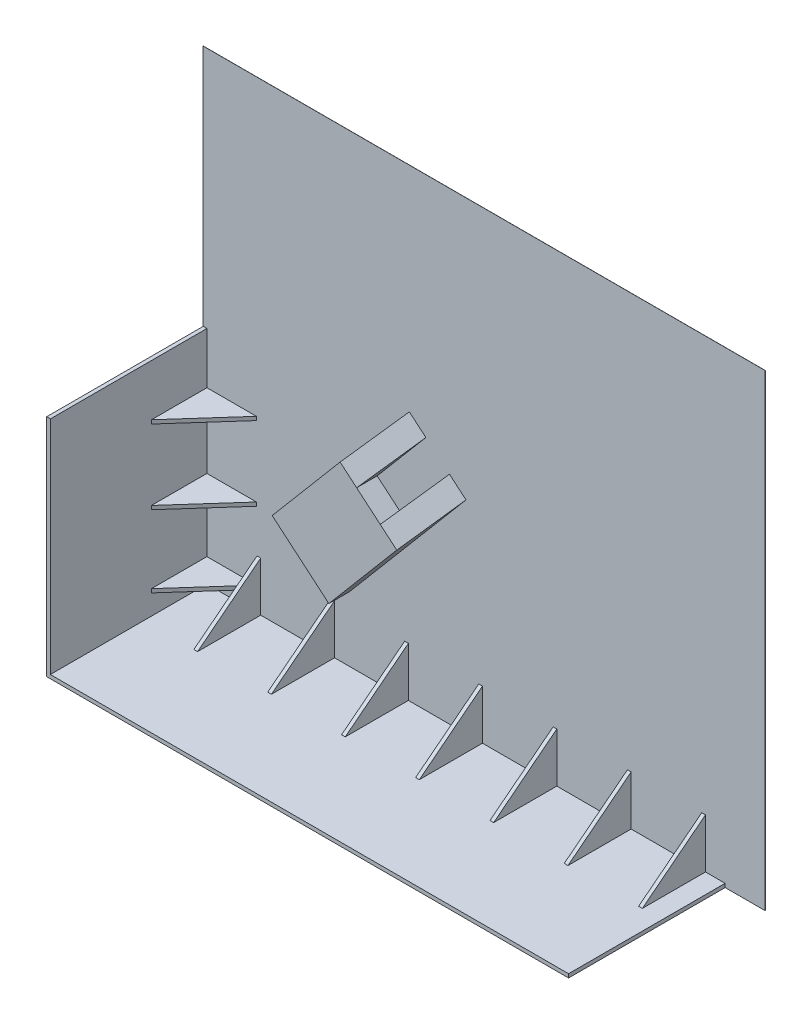
SolidWorks part; units mm, degrees
ref_plane "Front Plane" through (0, 0, 0) normal (0, 0, 1) x (1, 0, 0)
ref_plane "Top Plane" through (0, 0, 0) normal (0, 1, 0) x (1, 0, 0)
ref_plane "Right Plane" through (0, 0, 0) normal (1, 0, 0) x (0, 0, -1)
sketch "walls" plane through (0, 0, 0) normal (0, 0, 1) x (1, 0, 0)
  line L1 (0, 0) -> (4220, 0)
  line L2 (0, 0) -> (0, 30)
  line L3 (30, 30) -> (435, 30)
  line L4 (4220, 0) -> (4220, 30)
  line L5 (30, 1405) -> (30, 1820)
  line L6 (0, 30) -> (0, 1820)
  line L7 (0, 1820) -> (30, 1820)
  line L8 (30, 30) -> (30, 192.5)
  line L9 (30, 1405) -> (430, 1405)
  line L10 (30, 222.5) -> (30, 775)
  line L11 (30, 1375) -> (430, 1375)
  line L12 (430, 1405) -> (430, 1375)
  line L13 (30, 805) -> (430, 805)
  line L14 (30, 805) -> (30, 1375)
  line L15 (30, 775) -> (430, 775)
  line L16 (430, 805) -> (430, 775)
  line L17 (30, 222.5) -> (430, 222.5)
  line L18 (465, 30) -> (1032, 30)
  line L19 (30, 192.5) -> (430, 192.5)
  line L20 (430, 222.5) -> (430, 192.5)
  line L21 (1062, 30) -> (1629, 30)
  line L22 (435, 30) -> (435, 430)
  line L23 (435, 430) -> (465, 430)
  line L24 (465, 30) -> (465, 430)
  line L25 (1659, 30) -> (2228, 30)
  line L26 (1032, 30) -> (1032, 430)
  line L27 (1032, 430) -> (1062, 430)
  line L28 (1062, 30) -> (1062, 430)
  line L29 (2258, 30) -> (2829, 30)
  line L30 (1629, 30) -> (1629, 430)
  line L31 (1629, 430) -> (1659, 430)
  line L32 (1659, 30) -> (1659, 430)
  line L33 (2859, 30) -> (3430, 30)
  line L34 (2228, 30) -> (2228, 430)
  line L35 (2228, 430) -> (2258, 430)
  line L36 (2258, 30) -> (2258, 430)
  line L37 (3460, 30) -> (4031, 30)
  line L38 (2829, 30) -> (2829, 430)
  line L39 (2829, 430) -> (2859, 430)
  line L40 (2859, 30) -> (2859, 430)
  line L41 (4061, 30) -> (4220, 30)
  line L42 (3430, 30) -> (3430, 430)
  line L43 (3430, 430) -> (3460, 430)
  line L44 (3460, 30) -> (3460, 430)
  line L46 (4031, 30) -> (4031, 430)
  line L47 (4031, 430) -> (4061, 430)
  line L48 (4061, 30) -> (4061, 430)
  dimension "D1" = 30
  dimension "D2" = 4220
  dimension "D3" = 30
  dimension "D4" = 1790
  dimension "D5" = 415
  dimension "D6" = 30
  dimension "D7" = 30
  dimension "D8" = 30
  dimension "D9" = 570
  dimension "D10" = 552.5
  dimension "D11" = 30
  dimension "D12" = 400
  dimension "D13" = 405
  dimension "D14" = 400
  dimension "D15" = 400
  dimension "D16" = 400
  dimension "D17" = 30
  dimension "D18" = 30
  dimension "D19" = 30
  dimension "D20" = 30
  dimension "D21" = 30
  dimension "D22" = 30
  dimension "D23" = 567
  dimension "D24" = 567
  dimension "D25" = 569
  dimension "D26" = 571
  dimension "D27" = 571
  dimension "D28" = 571
sketch "stairs" plane through (5389.1447, -90.534, 0) normal (0, 0, 1) x (1, 0, 0)
  line L49 (0, 2425) -> (1250, 2425)
  line L50 (0, 2425) -> (0, 2380)
  line L51 (0, 2380) -> (1295, 2380)
  line L52 (1295, 2425) -> (1295, 2380)
  line L53 (1250, 2721) -> (814.6841, 2721)
  line L54 (1295, 2721) -> (1295, 2766)
  line L55 (1295, 2766) -> (814.6841, 2766)
  line L56 (814.6841, 2721) -> (814.6841, 2766)
  line L58 (1295, 2721) -> (1295, 2425)
  line L60 (1250, 2721) -> (1250, 2425)
  dimension "D29" = 45
  dimension "D31" = 1295
  dimension "D32" = 45
  dimension "D33" = 296
  dimension "D34" = 45
sketch "column" plane through (914.7087, 1935.0689, 0) normal (0, 0, 1) x (1, 0, 0)
  line L0 (5085, 2493.4255) -> (5585, 2493.4255)
  line L61 (5585, 2493.4255) -> (5585, 1993.4255)
  line L62 (5585, 1993.4255) -> (5285, 1993.4255)
  line L63 (5285, 1993.4255) -> (5285, 2193.4255)
  line L64 (5285, 2193.4255) -> (5085, 2193.4255)
  line L65 (5085, 2193.4255) -> (5085, 2493.4255)
  dimension "D35" = 200
  dimension "D36" = 300
  dimension "D37" = 500
  dimension "D38" = 200
extrude "Boss-Extrude1" add sketch "walls" along normal blind 1266
extrude "Boss-Extrude2" add sketch "column" along normal blind 2500
extrude "Boss-Extrude3" add sketch "stairs" along normal blind 902.5
sketch "large_wall_cut" plane through (4061, 0, 0) normal (1, 0, 0) x (0, 0, -1)
  line L0 (-1266, 30) -> (-1266, 430)
  line L1 (-1266, 430) -> (0, 430)
  line L2 (-1266, 430) -> (0, 430) construction
  line L3 (0, 30) -> (0, 430) construction
  line L4 (0, 430) -> (-510.6351, 30)
  line L5 (-1266, 30) -> (0, 30) construction
  line L6 (-510.6351, 30) -> (-1266, 30)
extrude "Cut-Extrude1" cut sketch "large_wall_cut" against normal blind 3630
sketch "small_wall_cut" plane through (0, 1405, 0) normal (0, 1, 0) x (1, 0, 0)
  line L0 (30, -1266) -> (430, -1266)
  line L1 (430, -1266) -> (430, 0)
  line L2 (430, 0) -> (30, -448.2809)
  line L3 (30, -1266) -> (30, 0) construction
  line L4 (30, -448.2809) -> (30, -1266)
extrude "Cut-Extrude3" cut sketch "small_wall_cut" against normal blind 1220
sketch "Sketch8" plane through (5389.1447, 2289.466, 0) normal (0, -1, 0) x (-1, 0, 0)
  line L0 (0, -902.5) -> (0, 0) construction
  line L1 (0, -285) -> (-485, -285)
  line L2 (0, -285) -> (0, 0)
  line L3 (0, 0) -> (-485, 0)
  line L4 (-485, -285) -> (-485, 0)
  line L5 (0, 0) -> (-1295, 0) construction
  dimension "D1" = 285
  dimension "D2" = 485
extrude "Cut-Extrude5" cut sketch "Sketch8" against normal blind 390
sketch "Sketch9" plane through (5389.1447, 2289.466, 0) normal (0, -1, 0) x (1, 0, 0)
  line L0 (485, 0) -> (1295, 0) construction
  line L1 (520, 0) -> (790, 0)
  line L2 (520, 0) -> (520, 285)
  line L3 (520, 285) -> (790, 285)
  line L4 (790, 0) -> (790, 285)
  line L5 (485, 0) -> (485, 285) construction
  line L6 (485, 285) -> (0, 285) construction
  dimension "D1" = 35
  dimension "D2" = 270
  dimension "D3" = 0
extrude "Cut-Extrude6" cut sketch "Sketch9" against normal blind 390
sketch "Sketch10" plane through (5389.1447, 2289.466, 0) normal (0, -1, 0) x (1, 0, 0)
  line L0 (790, 0) -> (1295, 0) construction
  line L1 (825, 0) -> (1295, 0)
  line L2 (825, 0) -> (825, 285)
  line L3 (825, 285) -> (1295, 285)
  line L4 (1295, 0) -> (1295, 285)
  line L5 (1295, 902.5) -> (1295, 0) construction
  line L6 (790, 0) -> (790, 285) construction
  line L7 (790, 285) -> (520, 285) construction
  dimension "D1" = 35
  dimension "D2" = 0
extrude "Cut-Extrude7" cut sketch "Sketch10" against normal blind 390
sketch "Sketch11" plane through (5389.1447, 2289.466, 0) normal (0, -1, 0) x (-1, 0, 0)
  line L0 (0, -902.5) -> (0, -285) construction
  line L1 (0, -852.5) -> (-485, -852.5)
  line L2 (0, -852.5) -> (0, -635)
  line L3 (0, -635) -> (-485, -635)
  line L4 (-485, -852.5) -> (-485, -635)
  line L5 (-485, 0) -> (-485, -285) construction
  line L6 (-485, -285) -> (0, -285) construction
  line L7 (0, -902.5) -> (-1295, -902.5) construction
  dimension "D1" = 0
  dimension "D2" = 350
  dimension "D3" = 50
extrude "Cut-Extrude8" cut sketch "Sketch11" against normal blind 390
sketch "Sketch12" plane through (5389.1447, 2289.466, 0) normal (0, -1, 0) x (1, 0, 0)
  line L0 (520, 285) -> (520, 0) construction
  line L1 (520, 852.5) -> (790, 852.5)
  line L2 (520, 852.5) -> (520, 635)
  line L3 (520, 635) -> (790, 635)
  line L4 (790, 852.5) -> (790, 635)
  line L5 (790, 0) -> (790, 285) construction
  line L6 (485, 852.5) -> (0, 852.5) construction
  line L7 (0, 635) -> (485, 635) construction
  dimension "D1" = 0
  dimension "D2" = 0
  dimension "D3" = 0
  dimension "D4" = 0
extrude "Cut-Extrude9" cut sketch "Sketch12" against normal blind 390
sketch "Sketch13" plane through (5389.1447, 2289.466, 0) normal (0, -1, 0) x (1, 0, 0)
  line L0 (1295, 902.5) -> (1295, 285) construction
  line L1 (825, 852.5) -> (1295, 852.5)
  line L2 (825, 852.5) -> (825, 635)
  line L3 (825, 635) -> (1295, 635)
  line L4 (1295, 852.5) -> (1295, 635)
  line L5 (825, 285) -> (825, 0) construction
  line L6 (520, 635) -> (790, 635) construction
  line L7 (790, 852.5) -> (520, 852.5) construction
  dimension "D1" = 0
  dimension "D2" = 0
  dimension "D3" = 0
extrude "Cut-Extrude10" cut sketch "Sketch13" against normal blind 390
sketch "Sketch14" plane through (6684.1447, -90.534, 0) normal (1, 0, 0) x (0, 0, -1)
  line L0 (-635, 2766) -> (-285, 2766) construction
  line L1 (-585, 2610.1685) -> (0, 2610.1685)
  line L2 (-585, 2610.1685) -> (-585, 2766)
  line L3 (-585, 2766) -> (0, 2766)
  line L4 (0, 2610.1685) -> (0, 2766)
  line L5 (0, 2766) -> (0, 2721) construction
  line L6 (-635, 2766) -> (-635, 2380) construction
  dimension "D1" = 0
  dimension "D2" = 0
  dimension "D3" = 50
extrude "Cut-Extrude11" cut sketch "Sketch14" against normal blind 499
sketch "Sketch15" plane through (0, 0, 0) normal (0, 0, -1) x (-1, 0, 0)
  line L1 (0, 0) -> (-6996.3137, 0)
  line L2 (0, 0) -> (0, 5079.0441)
  line L3 (0, 5079.0441) -> (-6996.3137, 5079.0441)
  line L4 (-6996.3137, 0) -> (-6996.3137, 5079.0441)
extrude "Boss-Extrude5" add sketch "Sketch15" along normal blind 1
sketch "Sketch16" plane through (0, 0, 0) normal (-1, 0, 0) x (0, 0, 1)
  line L0 (2500, 4428.4943) -> (2500, 4128.4943) construction
  line L1 (-1, 0) -> (2500, 0)
  line L2 (-1, 0) -> (-1, 2455.4181)
  line L3 (-1, 2455.4181) -> (2500, 2455.4181)
  line L4 (2500, 0) -> (2500, 2455.4181)
  dimension "D1" = 0
extrude "Boss-Extrude6" [suppressed] add sketch "Sketch16" along normal blind 1
sketch "Sketch17" [suppressed] plane through (0, 0, 0) normal (0, -1, 0) x (1, 0, 0)
  line L0 (6996.3137, -1) -> (6996.3137, 0) construction
  line L1 (-1, -1) -> (6996.3137, -1)
  line L2 (-1, -1) -> (-1, 2499)
  line L3 (-1, 2499) -> (6996.3137, 2499)
  line L4 (6996.3137, -1) -> (6996.3137, 2499)
  dimension "D1" = 2500
  dimension "D2" = 0
extrude "Boss-Extrude7" [suppressed] add sketch "Sketch17" along normal blind 1
sketch "Sketch18" plane through (-186.0466, 70.6596, 0) normal (0, 0, 1) x (0.9681, 0.2504, 0)
  line L1 (1445.0486, 124.0136) -> (2138.9909, 614.8742)
  line L2 (1445.0486, 124.0136) -> (1098.5588, 613.8552)
  line L3 (1098.5588, 613.8552) -> (1792.501, 1104.7158)
  line L4 (2037.9313, 757.7447) -> (1893.5605, 961.8453)
  line L5 (2138.9909, 614.8742) -> (2636.9965, 967.1389)
  line L7 (2037.9313, 757.7447) -> (2535.9369, 1110.0094)
  line L8 (2636.9965, 967.1389) -> (2535.9369, 1110.0094)
  line L9 (1792.501, 1104.7158) -> (2290.5066, 1456.9805)
  line L11 (1893.5605, 961.8453) -> (2391.5662, 1314.11)
  line L12 (2290.5066, 1456.9805) -> (2391.5662, 1314.11)
  dimension "D1" = 850
  dimension "D2" = 600
  dimension "D3" = 175
  dimension "D4" = 175
  dimension "D5" = 610
  dimension "D6" = 610
extrude "Boss-Extrude8" add sketch "Sketch18" along normal blind 166
sketch "Sketch20" plane through (424.6315, -71.7875, 0) normal (-0.7635, 0.6458, 0) x (0.6458, 0.7635, 0)
  line L0 (2425.7348, 0) -> (1815.7348, -166)
  line L1 (1815.7348, -166) -> (2425.7348, -166)
  line L2 (2425.7348, -166) -> (2425.7348, 0)
extrude "Cut-Extrude12" cut sketch "Sketch20" against normal blind 180
sketch "Sketch21" plane through (233.7566, 89.6645, 0) normal (0.7635, -0.6458, 0) x (-0.6458, -0.7635, 0)
  line L0 (-2425.7348, 0) -> (-1815.7348, -166)
  line L1 (-1815.7348, -166) -> (-2425.7348, -166)
  line L2 (-2425.7348, -166) -> (-2425.7348, 0)
extrude "Cut-Extrude13" cut sketch "Sketch21" against normal blind 180
sketch "Sketch25" plane through (0, 0, 0) normal (0, 0, 1) x (1, 0, 0)
  line L0 (6996.3137, 0) -> (4220, 0) construction
  line L1 (4462.64, 0) -> (6996.3137, 0)
  line L2 (4462.64, 0) -> (4462.64, 5079.0441)
  line L3 (4462.64, 5079.0441) -> (6996.3137, 5079.0441)
  line L4 (6996.3137, 0) -> (6996.3137, 5079.0441)
extrude "Cut-Extrude14" cut sketch "Sketch25" along normal blind 20000
sketch "Sketch26" plane through (0, 0, 0) normal (0, 0, 1) x (1, 0, 0)
  line L0 (0, 1820) -> (0, 5079.0441) construction
  line L1 (0, 3782.4248) -> (6996.3137, 3782.4248)
  line L2 (0, 3782.4248) -> (0, 5079.0441)
  line L3 (0, 5079.0441) -> (6996.3137, 5079.0441)
  line L4 (6996.3137, 3782.4248) -> (6996.3137, 5079.0441)
extrude "Cut-Extrude15" cut sketch "Sketch26" against normal blind 2000
sketch "Sketch27" plane through (0, 0, 0) normal (0, 0, 1) x (1, 0, 0)
  line L0 (0, 3782.4248) -> (6996.3137, 3782.4248) construction
  line L1 (6996.3137, 0) -> (4544.1408, 0)
  line L2 (6996.3137, 0) -> (6996.3137, 3782.4248)
  line L3 (6996.3137, 3782.4248) -> (4544.1408, 3782.4248)
  line L4 (4544.1408, 0) -> (4544.1408, 3782.4248)
extrude "Cut-Extrude16" cut sketch "Sketch27" against normal blind 2000
